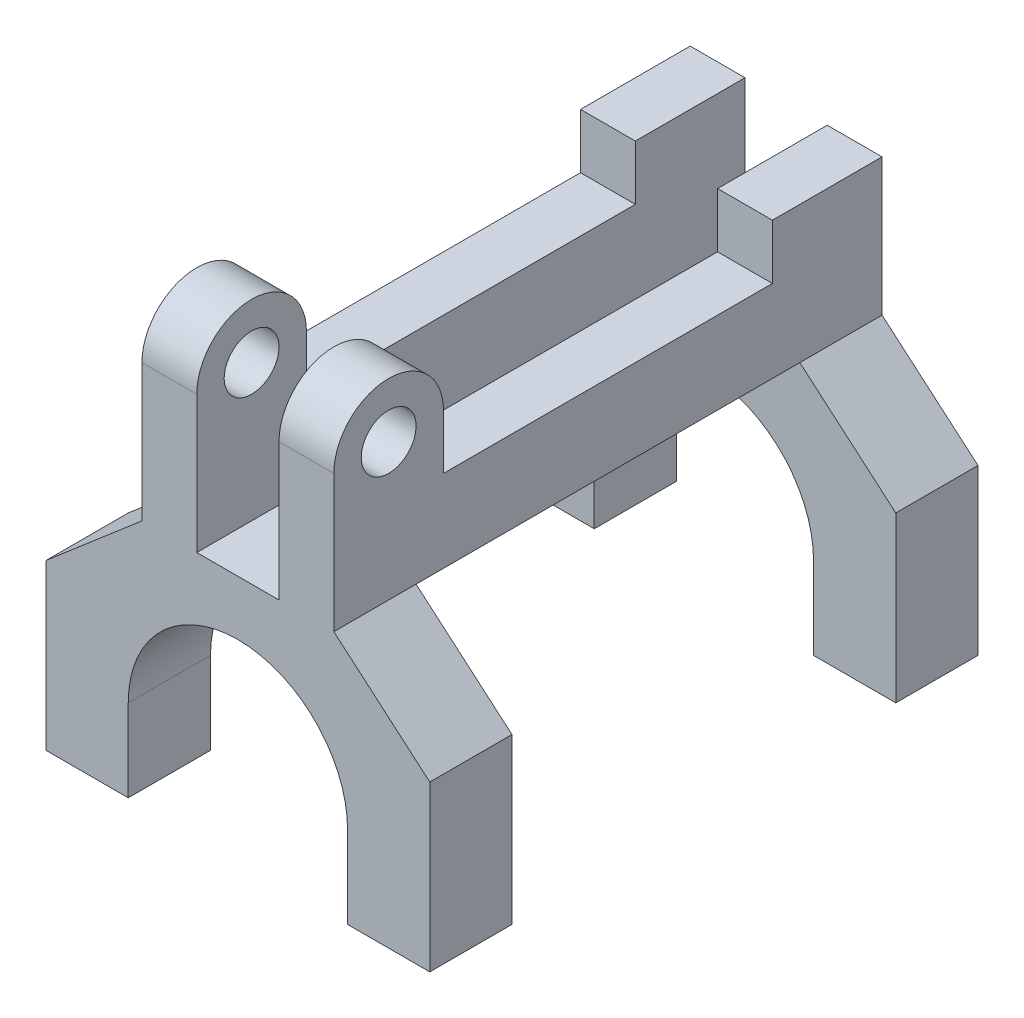
SolidWorks part; units mm, degrees
ref_plane "Front Plane" through (0, 0, 0) normal (0, 0, 1) x (1, 0, 0)
ref_plane "Top Plane" through (0, 0, 0) normal (0, 1, 0) x (1, 0, 0)
ref_plane "Right Plane" through (0, 0, 0) normal (1, 0, 0) x (0, 0, -1)
sketch "Sketch1" plane through (0, 0, 0) normal (0, 0, 1) x (1, 0, 0)
  line L2 (-44.45, -21.0397) -> (-44.45, -59.1397)
  line L3 (-44.45, -59.1397) -> (-25.4, -59.1397)
  line L4 (-25.4, -59.1397) -> (-25.4, -40.0897)
  line L6 (-25.4, -40.0897) -> (0, -40.0897) construction
  line L7 (0, -14.6897) -> (0, -40.0897) construction
  line L9 (-44.45, -21.0397) -> (-22.225, -1.9897)
  line L10 (-22.225, -1.9897) -> (22.225, -1.9897)
  line L11 (44.45, -21.0397) -> (22.225, -1.9897)
  line L12 (44.45, -21.0397) -> (44.45, -59.1397)
  line L13 (44.45, -59.1397) -> (25.4, -59.1397)
  line L14 (25.4, -59.1397) -> (25.4, -40.0897)
  arc A0 (-25.4, -40.0897) -> (25.4, -40.0897) centre (0, -40.0897) cw
  dimension "D1" = 25.4
  dimension "D2" = 19.05
  dimension "D3" = 38.1
  dimension "D4" = 19.05
  dimension "D5" = 44.45
  dimension "D6" = 90
  dimension "D7" = 57.15
extrude "Boss-Extrude1" add sketch "Sketch1" against normal blind 127 contours L11 L10 L9 L2 L3 L4 A0 L14 L13 L12
ref_plane "Plane1" through (44.45, 0, 0) normal (1, 0, 0) x (0, 0, -1)
sketch "Sketch2" plane through (44.45, 0, 0) normal (1, 0, 0) x (0, 0, -1)
  line L8 (127, -1.9897) -> (0, -1.9897) construction
  line L9 (19.05, -1.9897) -> (107.95, -1.9897)
  line L10 (19.05, -1.9897) -> (19.05, -59.1397)
  line L11 (19.05, -59.1397) -> (107.95, -59.1397)
  line L12 (107.95, -1.9897) -> (107.95, -59.1397)
  line L13 (127, -59.1397) -> (0, -59.1397) construction
  line L14 (0, -21.0397) -> (0, -1.9897) construction
  line L15 (127, -21.0397) -> (127, -59.1397) construction
  point P12 (19.05, -1.9897)
  dimension "D1" = 19.05
  dimension "D2" = 19.05
  dimension "D3" = 57.15
extrude "Cut-Extrude1" cut sketch "Sketch2" against normal blind 88.9
ref_plane "Plane2" through (22.225, 0, 0) normal (-1, 0, 0) x (0, 0, 1)
sketch "Sketch3" plane through (22.225, 0, 0) normal (-1, 0, 0) x (0, 0, 1)
  line L0 (0, -1.9897) -> (0, 29.7603)
  line L2 (-25.4, 29.7603) -> (-25.4, 17.0603)
  line L3 (-25.4, 17.0603) -> (-101.6, 17.0603)
  line L4 (-101.6, 17.0603) -> (-101.6, 29.7603)
  line L5 (-101.6, 29.7603) -> (-127, 29.7603)
  line L6 (-127, 29.7603) -> (-127, -1.9897)
  line L7 (-127, -1.9897) -> (0, -1.9897)
  arc A0 (-25.4, 29.7603) -> (0, 29.7603) centre (-12.7, 29.7603) cw
  circle A1 centre (-12.7, 29.7603) radius 6.35
  dimension "D5" = 12.7
  dimension "D4" = 12.7
  dimension "D1" = 31.75
  dimension "D2" = 25.4
  dimension "D3" = 12.7
  dimension "D6" = 31.75
  dimension "D7" = 25.4
extrude "Boss-Extrude2" add sketch "Sketch3" along normal blind 44.45
ref_plane "Plane3" through (0, 0, 0) normal (0, 0, 1) x (1, 0, 0)
sketch "Sketch4" plane through (0, 0, 0) normal (0, 0, 1) x (1, 0, 0)
  line L0 (22.225, 42.4603) -> (-22.225, 42.4603) construction
  line L1 (-9.525, 42.4603) -> (9.525, 42.4603)
  line L2 (-9.525, 42.4603) -> (-9.525, -1.9897)
  line L5 (-22.225, -1.9897) -> (-22.225, 29.7603) construction
  line L6 (9.525, 42.4603) -> (9.525, -1.9897)
  line L7 (22.225, 27.8115) -> (22.225, -27.8115) construction
  line L8 (-22.225, -1.9897) -> (22.225, -1.9897) construction
  line L9 (-9.525, -1.9897) -> (9.525, -1.9897)
  dimension "D1" = 12.7
  dimension "D2" = 12.7
extrude "Cut-Extrude2" cut sketch "Sketch4" against normal blind 127
